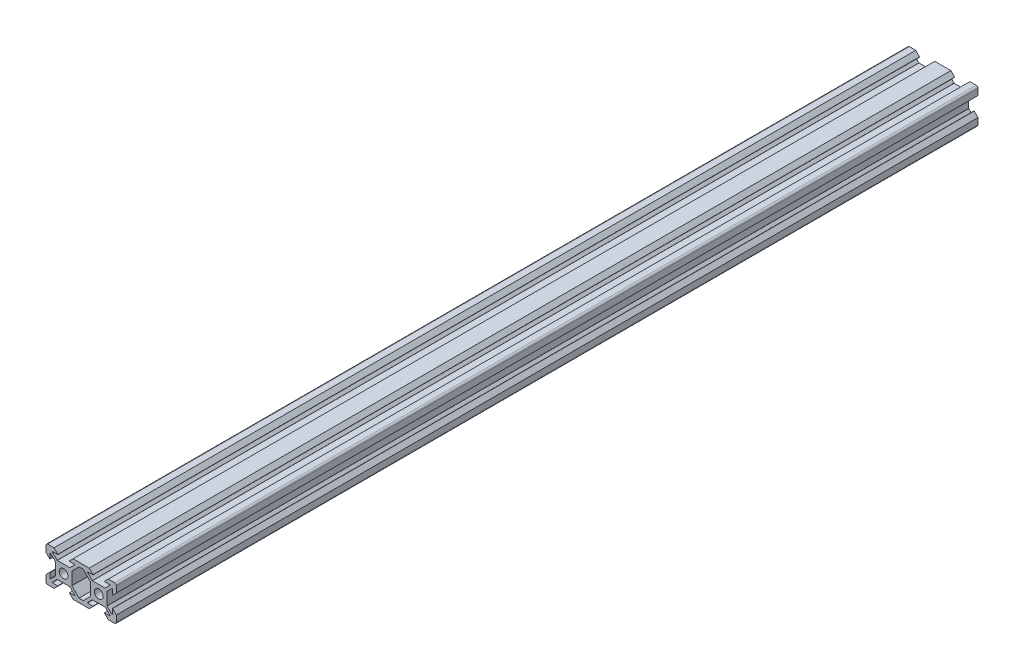
SolidWorks part; units mm, degrees
ref_plane "Alzado" through (0, 0, 0) normal (0, 0, 1) x (1, 0, 0)
ref_plane "Planta" through (0, 0, 0) normal (0, 1, 0) x (1, 0, 0)
ref_plane "Vista lateral" through (0, 0, 0) normal (1, 0, 0) x (0, 0, -1)
sketch "Croquis1" plane through (0, 0, 0) normal (0, 1, 0) x (1, 0, 0)
  line L0 (0, 245) -> (0, -245)
  dimension "D1" = 490
other "Miembro estructural1"
ref_plane "Plano1" through (0, 0, -245) normal (0, 0, 1) x (1, 0, 0)
sketch "Croquis4" plane through (0, 0, -245) normal (0, 0, 1) x (1, 0, 0)
  line L0 (0, 10) -> (0, 7.6897) construction
  line L1 (-19, -10) -> (-15.4103, -10)
  line L2 (-20, -9) -> (-20, -5.4103)
  line L3 (-19, 10) -> (-15.4103, 10)
  line L5 (20, 5.4103) -> (20, 9)
  line L6 (20, 5.4103) -> (17.8604, 3.2707)
  line L8 (17.6897, 3.3414) -> (17.6897, 6.3586)
  line L9 (-15.4103, 10) -> (-13.2707, 7.8604)
  line L10 (-13.3414, 7.6897) -> (-16.3586, 7.6897)
  line L11 (-16.4293, 7.519) -> (-13.6293, 4.719)
  line L12 (-13.5586, 4.6897) -> (-6.4414, 4.6897)
  line L13 (-3.5707, 7.519) -> (-6.3707, 4.719)
  line L14 (-6.6586, 7.6897) -> (-3.6414, 7.6897)
  line L15 (-4.5897, 10) -> (-6.7293, 7.8604)
  line L16 (-4.5897, 10) -> (4.5897, 10)
  line L17 (17.519, 6.4293) -> (14.719, 3.6293)
  line L18 (14.6897, -3.5586) -> (14.6897, 3.5586)
  line L19 (-2.481, 6.4293) -> (-5.281, 3.6293)
  line L20 (-5.3103, 3.5586) -> (-5.3103, -3.5586)
  line L21 (-2.481, -6.4293) -> (-5.281, -3.6293)
  line L22 (17.519, -6.4293) -> (14.719, -3.6293)
  line L23 (17.6897, -3.3414) -> (17.6897, -6.3586)
  line L24 (-4.5897, -10) -> (-6.7293, -7.8604)
  line L25 (-6.6586, -7.6897) -> (-3.6414, -7.6897)
  line L26 (-3.5707, -7.519) -> (-6.3707, -4.719)
  line L27 (-6.4414, -4.6897) -> (-13.5586, -4.6897)
  line L28 (-16.4293, -7.519) -> (-13.6293, -4.719)
  line L29 (-13.3414, -7.6897) -> (-16.3586, -7.6897)
  line L30 (-15.4103, -10) -> (-13.2707, -7.8604)
  line L31 (-20, -5.4103) -> (-17.8604, -3.2707)
  line L32 (-17.6897, -3.3414) -> (-17.6897, -6.3586)
  line L33 (-17.519, -6.4293) -> (-14.719, -3.6293)
  line L34 (-14.6897, -3.5586) -> (-14.6897, 3.5586)
  line L35 (-17.519, 6.4293) -> (-14.719, 3.6293)
  line L36 (-17.6897, 3.3414) -> (-17.6897, 6.3586)
  line L37 (-20, 5.4103) -> (-17.8604, 3.2707)
  line L38 (-20, 5.4103) -> (-20, 9)
  line L39 (-4.5897, -10) -> (4.5897, -10)
  line L40 (-2.3103, 3.3414) -> (-2.3103, 6.3586) [skipped]
  line L41 (0, 5.4103) -> (-2.1396, 3.2707) [skipped]
  line L42 (-2.3103, -3.3414) -> (-2.3103, -6.3586) [skipped]
  line L43 (0, -5.4103) -> (-2.1396, -3.2707) [skipped]
  line L44 (20, -5.4103) -> (17.8604, -3.2707)
  line L45 (15.4103, -10) -> (13.2707, -7.8604)
  line L46 (13.3414, -7.6897) -> (16.3586, -7.6897)
  line L47 (16.4293, -7.519) -> (13.6293, -4.719)
  line L48 (6.4414, -4.6897) -> (13.5586, -4.6897)
  line L49 (3.5707, -7.519) -> (6.3707, -4.719)
  line L50 (6.6586, -7.6897) -> (3.6414, -7.6897)
  line L51 (4.5897, -10) -> (6.7293, -7.8604)
  line L52 (2.481, -6.4293) -> (5.281, -3.6293)
  line L53 (5.3103, 3.5586) -> (5.3103, -3.5586)
  line L54 (2.481, 6.4293) -> (5.281, 3.6293)
  line L55 (4.5897, 10) -> (6.7293, 7.8604)
  line L56 (6.6586, 7.6897) -> (3.6414, 7.6897)
  line L57 (3.5707, 7.519) -> (6.3707, 4.719)
  line L58 (13.5586, 4.6897) -> (6.4414, 4.6897)
  line L59 (16.4293, 7.519) -> (13.6293, 4.719)
  line L60 (13.3414, 7.6897) -> (16.3586, 7.6897)
  line L61 (15.4103, 10) -> (13.2707, 7.8604)
  line L62 (19, 10) -> (15.4103, 10)
  line L63 (20, -9) -> (20, -5.4103)
  line L64 (19, -10) -> (15.4103, -10)
  line L65 (-3.6414, -7.6897) -> (3.6414, -7.6897) construction
  line L69 (-2.481, -6.4293) -> (-1.2206, -7.6897)
  line L70 (-1.2206, -7.6897) -> (1.2206, -7.6897)
  line L71 (2.481, -6.4293) -> (1.2206, -7.6897)
  line L72 (-2.481, 6.4293) -> (-1.2206, 7.6897)
  line L73 (-1.2206, 7.6897) -> (1.2206, 7.6897)
  line L74 (1.2206, 7.6897) -> (2.481, 6.4293)
  arc A0 (17.6897, 3.3414) -> (17.8604, 3.2707) centre (17.7897, 3.3414) ccw
  arc A1 (17.519, 6.4293) -> (17.6897, 6.3586) centre (17.5897, 6.3586) cw
  arc A2 (-19, -10) -> (-20, -9) centre (-19, -9) cw
  arc A3 (-20, 9) -> (-19, 10) centre (-19, 9) cw
  circle A4 centre (-10, 0) radius 2.5
  arc A5 (14.719, 3.6293) -> (14.6897, 3.5586) centre (14.7897, 3.5586) ccw
  arc A6 (-6.6586, 7.6897) -> (-6.7293, 7.8604) centre (-6.6586, 7.7897) cw
  arc A7 (-13.2707, 7.8604) -> (-13.3414, 7.6897) centre (-13.3414, 7.7897) cw
  arc A8 (-3.5707, 7.519) -> (-3.6414, 7.6897) centre (-3.6414, 7.5897) ccw
  arc A9 (-6.3707, 4.719) -> (-6.4414, 4.6897) centre (-6.4414, 4.7897) cw
  arc A10 (-13.6293, 4.719) -> (-13.5586, 4.6897) centre (-13.5586, 4.7897) ccw
  arc A11 (-16.3586, 7.6897) -> (-16.4293, 7.519) centre (-16.3586, 7.5897) ccw
  arc A12 (14.719, -3.6293) -> (14.6897, -3.5586) centre (14.7897, -3.5586) cw
  arc A13 (17.6897, -6.3586) -> (17.519, -6.4293) centre (17.5897, -6.3586) cw
  arc A14 (-5.281, 3.6293) -> (-5.3103, 3.5586) centre (-5.2103, 3.5586) ccw
  arc A15 (-5.281, -3.6293) -> (-5.3103, -3.5586) centre (-5.2103, -3.5586) cw
  arc A16 (17.8604, -3.2707) -> (17.6897, -3.3414) centre (17.7897, -3.3414) ccw
  arc A17 (13.3414, -7.6897) -> (13.2707, -7.8604) centre (13.3414, -7.7897) ccw
  arc A18 (-6.7293, -7.8604) -> (-6.6586, -7.6897) centre (-6.6586, -7.7897) cw
  arc A19 (-3.6414, -7.6897) -> (-3.5707, -7.519) centre (-3.6414, -7.5897) ccw
  arc A20 (-6.3707, -4.719) -> (-6.4414, -4.6897) centre (-6.4414, -4.7897) ccw
  arc A21 (-13.6293, -4.719) -> (-13.5586, -4.6897) centre (-13.5586, -4.7897) cw
  arc A22 (-16.4293, -7.519) -> (-16.3586, -7.6897) centre (-16.3586, -7.5897) ccw
  arc A23 (-13.3414, -7.6897) -> (-13.2707, -7.8604) centre (-13.3414, -7.7897) cw
  arc A24 (-17.8604, -3.2707) -> (-17.6897, -3.3414) centre (-17.7897, -3.3414) cw
  arc A25 (-17.6897, -6.3586) -> (-17.519, -6.4293) centre (-17.5897, -6.3586) ccw
  arc A26 (-14.719, -3.6293) -> (-14.6897, -3.5586) centre (-14.7897, -3.5586) ccw
  arc A27 (-14.719, 3.6293) -> (-14.6897, 3.5586) centre (-14.7897, 3.5586) cw
  arc A28 (-17.519, 6.4293) -> (-17.6897, 6.3586) centre (-17.5897, 6.3586) ccw
  arc A29 (-17.6897, 3.3414) -> (-17.8604, 3.2707) centre (-17.7897, 3.3414) cw
  arc A30 (-2.3103, 6.3586) -> (-2.481, 6.4293) centre (-2.4103, 6.3586) ccw [skipped]
  arc A31 (-2.1396, 3.2707) -> (-2.3103, 3.3414) centre (-2.2103, 3.3414) cw [skipped]
  arc A32 (-2.481, -6.4293) -> (-2.3103, -6.3586) centre (-2.4103, -6.3586) ccw [skipped]
  arc A33 (-2.3103, -3.3414) -> (-2.1396, -3.2707) centre (-2.2103, -3.3414) cw [skipped]
  arc A34 (16.4293, -7.519) -> (16.3586, -7.6897) centre (16.3586, -7.5897) cw
  arc A35 (13.6293, -4.719) -> (13.5586, -4.6897) centre (13.5586, -4.7897) ccw
  arc A36 (6.3707, -4.719) -> (6.4414, -4.6897) centre (6.4414, -4.7897) cw
  arc A37 (3.6414, -7.6897) -> (3.5707, -7.519) centre (3.6414, -7.5897) cw
  arc A38 (6.7293, -7.8604) -> (6.6586, -7.6897) centre (6.6586, -7.7897) ccw
  arc A39 (5.281, -3.6293) -> (5.3103, -3.5586) centre (5.2103, -3.5586) ccw
  arc A40 (5.281, 3.6293) -> (5.3103, 3.5586) centre (5.2103, 3.5586) cw
  arc A41 (16.3586, 7.6897) -> (16.4293, 7.519) centre (16.3586, 7.5897) cw
  arc A42 (13.6293, 4.719) -> (13.5586, 4.6897) centre (13.5586, 4.7897) cw
  arc A43 (6.3707, 4.719) -> (6.4414, 4.6897) centre (6.4414, 4.7897) ccw
  arc A44 (3.5707, 7.519) -> (3.6414, 7.6897) centre (3.6414, 7.5897) cw
  arc A45 (13.2707, 7.8604) -> (13.3414, 7.6897) centre (13.3414, 7.7897) ccw
  arc A46 (6.6586, 7.6897) -> (6.7293, 7.8604) centre (6.6586, 7.7897) ccw
  circle A47 centre (10, 0) radius 2.5
  arc A48 (20, 9) -> (19, 10) centre (19, 9) ccw
  arc A49 (19, -10) -> (20, -9) centre (19, -9) ccw
  point P0 (0, 0)
  point P2 (0, 0)
  point P34 (-10, 4.6897)
  point P39 (-6.9, 7.6897)
  point P42 (-13.1, 7.6897)
  point P45 (-3.4, 7.6897)
  point P48 (-6.4, 4.6897)
  point P51 (-13.6, 4.6897)
  point P54 (-16.6, 7.6897)
  point P118 (-10, 0)
  point P188 (16.6, 7.6897)
  point P189 (13.6, 4.6897)
  point P190 (6.4, 4.6897)
  point P191 (3.4, 7.6897)
  point P192 (13.1, 7.6897)
  point P193 (6.9, 7.6897)
  point P194 (10, 4.6897)
  point P200 (0, -7.6897)
  dimension "D5" = 5
  dimension "D10" = 0.1
  dimension "D11" = 0.1
  dimension "D7" = 3
  dimension "D8" = 3.5
  dimension "D9" = 45
  dimension "D12" = 4
